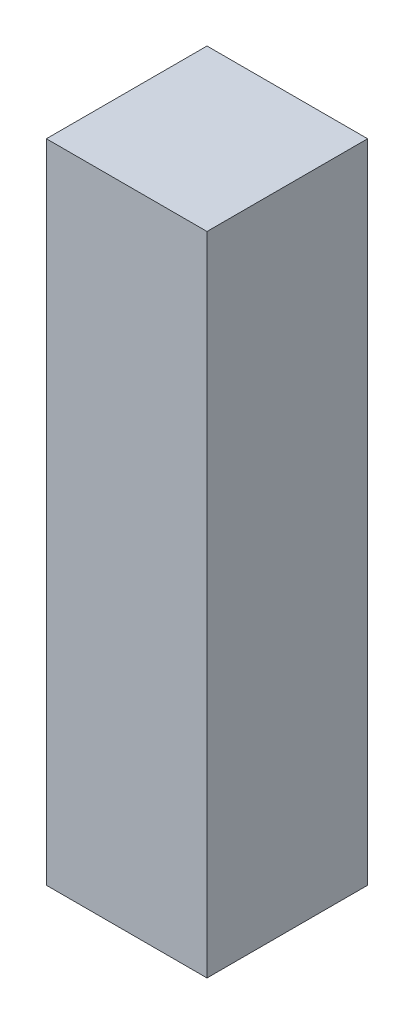
SolidWorks part; units mm, degrees
ref_plane "前视基准面" through (0, 0, 0) normal (0, 0, 1) x (1, 0, 0)
ref_plane "上视基准面" through (0, 0, 0) normal (0, 1, 0) x (1, 0, 0)
ref_plane "右视基准面" through (0, 0, 0) normal (1, 0, 0) x (0, 0, -1)
other "Configuration Table"
sketch "草图1" plane through (0, 0, 0) normal (0, 1, 0) x (1, 0, 0)
  line L1 (-10, 10) -> (10, 10)
  line L2 (-10, 10) -> (-10, -10)
  line L3 (-10, -10) -> (10, -10)
  line L4 (10, 10) -> (10, -10)
  line L5 (-10, 10) -> (10, -10) construction
  line L6 (-10, -10) -> (10, 10) construction
  point P0 (0, 0)
  dimension "D1" = 20
  dimension "D2" = 20
extrude "凸台-拉伸1" add sketch "草图1" along normal blind 80.5
